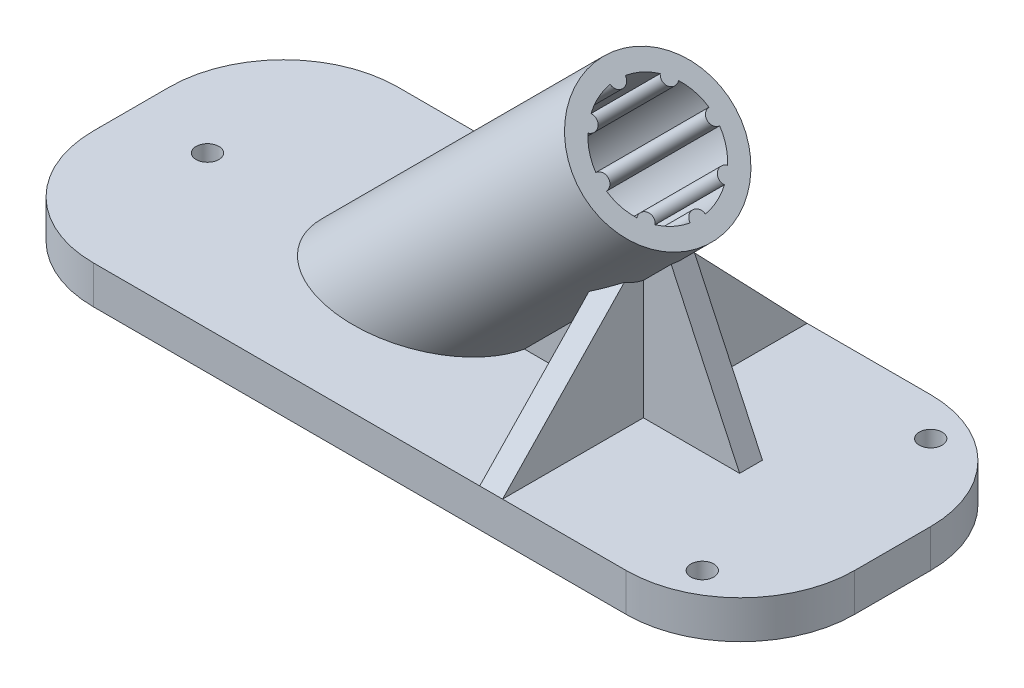
SolidWorks part; units mm, degrees
ref_plane "Front Plane" through (0, 0, 0) normal (0, 0, 1) x (1, 0, 0)
ref_plane "Top Plane" through (0, 0, 0) normal (0, 1, 0) x (1, 0, 0)
ref_plane "Right Plane" through (0, 0, 0) normal (1, 0, 0) x (0, 0, -1)
sketch "Sketch1" plane through (0, 0, 0) normal (0, 1, 0) x (1, 0, 0)
  line L1 (35, 20) -> (-35, 20)
  line L2 (50, 5) -> (50, -5)
  line L3 (35, -20) -> (-35, -20)
  line L4 (-50, 5) -> (-50, -5)
  line L5 (50, 20) -> (-50, -20) construction
  line L6 (50, -20) -> (-50, 20) construction
  arc A0 (-35, 20) -> (-50, 5) centre (-35, 5) ccw
  arc A1 (50, -5) -> (35, -20) centre (35, -5) cw
  arc A2 (35, 20) -> (50, 5) centre (35, 5) cw
  arc A3 (-35, -20) -> (-50, -5) centre (-35, -5) cw
  point P0 (0, 0)
  dimension "D3" = 15
  dimension "D1" = 100
  dimension "D2" = 40
extrude "Boss-Extrude1" add sketch "Sketch1" along normal blind 5
sketch "Sketch2" plane through (0, 0, 0) normal (0, 0, 1) x (1, 0, 0)
  line L0 (-30, 0) -> (12.0711, 42.0711)
  line L1 (-35, 0) -> (35, 0) construction
  line L2 (12.0711, 42.0711) -> (19.1421, 35)
  line L3 (19.1421, 35) -> (-15.8579, 0)
  line L4 (-35, 5) -> (35, 5) construction
  line L5 (-15.8579, 0) -> (-30, 0)
  dimension "D1" = 10
  dimension "D2" = 30
  dimension "D3" = 45
  dimension "D4" = 20
revolve "Revolve2" add sketch "Sketch2" angle 360 about L3
sketch "Sketch3" plane through (0, 0, 0) normal (0, -1, 0) x (1, 0, 0)
  line L1 (4.0451, 13.8917) -> (-32.3608, 13.8917)
  line L2 (4.0451, 13.8917) -> (4.0451, -13.8917)
  line L3 (4.0451, -13.8917) -> (-32.3608, -13.8917)
  line L4 (-32.3608, 13.8917) -> (-32.3608, -13.8917)
  line L5 (4.0451, 13.8917) -> (-32.3608, -13.8917) construction
  line L6 (4.0451, -13.8917) -> (-32.3608, 13.8917) construction
  point P0 (-14.1579, 0)
extrude "Cut-Extrude1" cut sketch "Sketch3" along normal blind 36
sketch "Sketch4" plane through (27.0711, 27.0711, 0) normal (0.7071, 0.7071, 0) x (0, 0, -1)
  circle A0 centre (0, 11.2132) radius 7.5
  dimension "D1" = 15
extrude "Cut-Extrude2" cut sketch "Sketch4" against normal up to surface (49.9264 mm away)
sketch "Sketch5" plane through (27.0711, 27.0711, 0) normal (0.7071, 0.7071, 0) x (0, 0, -1)
  circle A0 centre (7.5, 11.2132) radius 1
  circle A1 centre (0, 11.2132) radius 7.5 construction
  circle A2 centre (0, 11.2132) radius 7.5 construction
  circle A3 centre (5.3033, 5.9099) radius 1
  circle A4 centre (0, 3.7132) radius 1
  circle A5 centre (-5.3033, 5.9099) radius 1
  circle A6 centre (-7.5, 11.2132) radius 1
  circle A7 centre (-5.3033, 16.5165) radius 1
  circle A8 centre (0, 18.7132) radius 1
  circle A9 centre (5.3033, 16.5165) radius 1
  point P22 (0, 11.2132)
  dimension "D1" = 2
  dimension "D2" = 8
extrude "Boss-Extrude2" add sketch "Sketch5" against normal up to surface (43.4264 mm away)
sketch "Sketch6" plane through (0, 0, 0) normal (0, 0, 1) x (1, 0, 0)
  line L0 (23.0054, 23) -> (30, 8)
  line L1 (50, 5) -> (50, 0) construction
  line L2 (50, 5) -> (35, 5) construction
  line L3 (-35, 5) -> (35, 5) construction
  point P4 (0, 0)
  point P6 (35, 5)
  dimension "D1" = 15
  dimension "D2" = 20
  dimension "D3" = 3
  dimension "D4" = 115
rib "Rib2" sketch "Sketch6" sketch "Sketch6" thickness 3 extrusion direction parallel to sketch draft on no parameters "D1"=3
ref_plane "Plane1" through (17.2616, 0, 0) normal (1, 0, 0) x (0, 0, -1)
sketch "Sketch7" plane through (17.2616, 0, 0) normal (1, 0, 0) x (0, 0, -1)
  line L0 (-1.5, 24.2829) -> (-20, 5)
rib "Rib3" sketch "Sketch7" sketch "Sketch7" thickness 3 extrusion direction parallel to sketch draft on no parameters "D1"=3
sketch "Sketch9" plane through (17.2616, 0, 0) normal (1, 0, 0) x (0, 0, -1)
  line L0 (1.5, 24.2829) -> (20, 5)
rib "Rib4" sketch "Sketch9" sketch "Sketch9" thickness 3 extrusion direction parallel to sketch draft on no parameters "D1"=3
sketch "Sketch10" plane through (0, 0, 0) normal (0, -1, 0) x (1, 0, 0)
  line L1 (40, 15) -> (-40, 15) construction
  line L2 (40, 15) -> (40, -15) construction
  line L3 (40, -15) -> (-40, -15) construction
  line L4 (-40, 15) -> (-40, -15) construction
  line L5 (40, 15) -> (-40, -15) construction
  line L6 (40, -15) -> (-40, 15) construction
  circle A0 centre (-40, 0) radius 1.5
  circle A1 centre (40, 15) radius 1.5
  circle A2 centre (40, -15) radius 1.5
  point P0 (0, 0)
  dimension "D3" = 3
  dimension "D1" = 80
  dimension "D2" = 30
extrude "Cut-Extrude3" cut sketch "Sketch10" against normal up to surface (5 mm away) up to face at (-13.5043, 5, 0)
